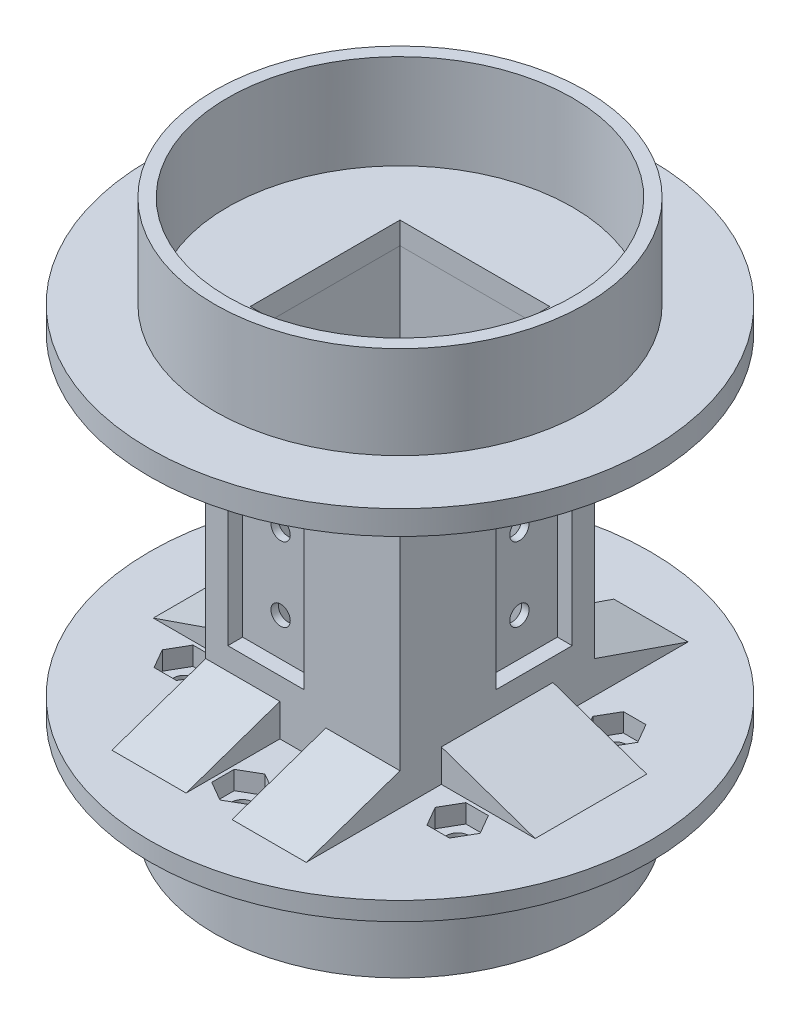
SolidWorks part; units mm, degrees
other "Markup1"
sketch "Sketch32" plane through (-67.5, -120, 67.5) normal (-0.5, 0, 0.866) x (0.866, 0, 0.5)
material "PLA"
ref_plane "Front Plane" through (0, 0, 0) normal (0, 0, 1) x (1, 0, 0)
ref_plane "Top Plane" through (0, 0, 0) normal (0, 1, 0) x (1, 0, 0)
ref_plane "Right Plane" through (0, 0, 0) normal (1, 0, 0) x (0, 0, -1)
sketch "Sketch1" plane through (0, 0, 0) normal (0, 1, 0) x (1, 0, 0)
  circle A0 centre (0, 0) radius 51.5
  circle A1 centre (0, 0) radius 46.5
  dimension "D1" = 103
  dimension "D2" = 93
extrude "Boss-Extrude1" add sketch "Sketch1" along normal blind 41
sketch "Sketch2" plane through (0, 0, 0) normal (0, -1, 0) x (1, 0, 0)
  circle A0 centre (0, 0) radius 46.5
  circle A1 centre (0, 0) radius 75
  dimension "D1" = 150
extrude "Boss-Extrude2" add sketch "Sketch2" along normal blind 5
sketch "Sketch3" plane through (0, -5, 0) normal (0, -1, 0) x (1, 0, 0)
  line L5 (-20.2, -20.2) -> (20.2, 20.2) construction
  line L6 (-20.2, 20.2) -> (20.2, -20.2) construction
  circle A0 centre (0, 0) radius 46.5
  point P0 (0, 0)
  dimension "D1" = 40.4
  dimension "D2" = 40.4
extrude "Boss-Extrude3" add sketch "Sketch3" against normal up to surface (5 mm away) up to face at (0, 0, 51.5)
sketch "Sketch4" plane through (0, 0, 0) normal (0, 1, 0) x (1, 0, 0)
  line L1 (-20.2, -20.2) -> (20.2, -20.2)
  line L2 (-20.2, -20.2) -> (-20.2, 20.2)
  line L3 (-20.2, 20.2) -> (20.2, 20.2)
  line L4 (20.2, -20.2) -> (20.2, 20.2)
  line L5 (-20.2, -20.2) -> (20.2, 20.2) construction
  line L6 (-20.2, 20.2) -> (20.2, -20.2) construction
  point P0 (0, 0)
  dimension "D1" = 40.4
  dimension "D2" = 40.4
extrude "Cut-Extrude1" cut sketch "Sketch4" against normal blind 6
sketch "Sketch5" plane through (0, -5, 0) normal (0, -1, 0) x (1, 0, 0)
  line L1 (-20.2, -20.2) -> (20.2, -20.2)
  line L2 (-20.2, -20.2) -> (-20.2, 20.2)
  line L3 (-20.2, 20.2) -> (20.2, 20.2)
  line L4 (20.2, -20.2) -> (20.2, 20.2)
  line L5 (-20.2, -20.2) -> (20.2, 20.2) construction
  line L6 (-20.2, 20.2) -> (20.2, -20.2) construction
  line L7 (-26.2, -26.2) -> (26.2, -26.2)
  line L8 (-26.2, -26.2) -> (-26.2, 26.2)
  line L9 (-26.2, 26.2) -> (26.2, 26.2)
  line L10 (26.2, -26.2) -> (26.2, 26.2)
  line L11 (-26.2, -26.2) -> (26.2, 26.2) construction
  line L12 (-26.2, 26.2) -> (26.2, -26.2) construction
  point P0 (0, 0)
  point P7 (0, 0)
  point P12 (-20.2, 0)
  point P13 (-26.2, 0)
  dimension "D1" = 6
  dimension "D2" = 6
extrude "Boss-Extrude4" add sketch "Sketch5" along normal blind 80
sketch "Sketch8" plane through (0, -85, 0) normal (0, -1, 0) x (1, 0, 0)
  line L1 (-26.2, -26.2) -> (26.2, -26.2)
  line L2 (-26.2, -26.2) -> (-26.2, 26.2)
  line L3 (-26.2, 26.2) -> (26.2, 26.2)
  line L4 (26.2, -26.2) -> (26.2, 26.2)
  line L5 (-26.2, -26.2) -> (26.2, 26.2) construction
  line L6 (-26.2, 26.2) -> (26.2, -26.2) construction
  point P0 (0, 0)
extrude "Boss-Extrude5" add sketch "Sketch8" along normal blind 5
sketch "Sketch9" plane through (0, 0, 0) normal (0, 1, 0) x (1, 0, 0)
  circle A0 centre (0, 0) radius 75
  circle A1 centre (0, 0) radius 51.5
extrude "Cut-Extrude4" cut sketch "Sketch9" against normal blind 1
sketch "Sketch10" plane through (0, -5, 0) normal (0, -1, 0) x (1, 0, 0)
  line L1 (-26.2, -26.2) -> (26.2, -26.2)
  line L2 (-26.2, -26.2) -> (-26.2, 26.2)
  line L3 (-26.2, 26.2) -> (26.2, 26.2)
  line L4 (26.2, -26.2) -> (26.2, 26.2)
  line L5 (-26.2, -26.2) -> (26.2, 26.2) construction
  line L6 (-26.2, 26.2) -> (26.2, -26.2) construction
  circle A0 centre (0, 0) radius 75
extrude "Boss-Extrude6" add sketch "Sketch10" along normal blind 1
sketch "Sketch11" plane through (0, 41, 0) normal (0, 1, 0) x (1, 0, 0)
  circle A0 centre (0, 0) radius 46.5
  circle A1 centre (0, 0) radius 51.5
extrude "Cut-Extrude5" cut sketch "Sketch11" against normal blind 13 and the other way through all
sketch "Sketch12" plane through (0, -85, 0) normal (0, 1, 0) x (1, 0, 0)
  line L1 (-20.2, -20.2) -> (20.2, -20.2)
  line L2 (-20.2, -20.2) -> (-20.2, 20.2)
  line L3 (-20.2, 20.2) -> (20.2, 20.2)
  line L4 (20.2, -20.2) -> (20.2, 20.2)
  line L5 (-20.2, -20.2) -> (20.2, 20.2) construction
  line L6 (-20.2, 20.2) -> (20.2, -20.2) construction
  point P0 (0, 0)
extrude "Cut-Extrude6" cut sketch "Sketch12" against normal blind 1
sketch "Sketch13" plane through (0, -90, 0) normal (0, -1, 0) x (1, 0, 0)
  line L1 (-26.2, -26.2) -> (26.2, -26.2)
  line L2 (-26.2, -26.2) -> (-26.2, 26.2)
  line L3 (-26.2, 26.2) -> (26.2, 26.2)
  line L4 (26.2, -26.2) -> (26.2, 26.2)
  line L5 (-26.2, -26.2) -> (26.2, 26.2) construction
  line L6 (-26.2, 26.2) -> (26.2, -26.2) construction
  point P0 (0, 0)
extrude "Boss-Extrude7" add sketch "Sketch13" along normal blind 1
sketch "Sketch6" plane through (0, 0, 26.2) normal (0, 0, 1) x (1, 0, 0)
  line L0 (-10, -6) -> (-10, -86) construction
  line L3 (26.2, -6) -> (-26.2, -6) construction
  line L4 (-20.25, -76.25) -> (0.25, -76.25)
  line L5 (-20.25, -76.25) -> (-20.25, -15.75)
  line L6 (-20.25, -15.75) -> (0.25, -15.75)
  line L7 (0.25, -76.25) -> (0.25, -15.75)
  line L8 (-20.25, -76.25) -> (0.25, -15.75) construction
  line L9 (-20.25, -15.75) -> (0.25, -76.25) construction
  line L10 (-26.2, -91) -> (-26.2, -6) construction
  point P6 (-10, -46)
  dimension "D1" = 20.5
  dimension "D2" = 60.5
  dimension "D3" = 9.75
  dimension "D4" = 5.95
extrude "Cut-Extrude2" cut sketch "Sketch6" against normal blind 4
sketch "Sketch7" plane through (0, 0, 22.2) normal (0, 0, 1) x (1, 0, 0)
  line L0 (0.25, -15.75) -> (-20.25, -15.75) construction
  circle A0 centre (-10, -26) radius 2.6
  circle A1 centre (-10, -46) radius 2.6
  circle A2 centre (-10, -66) radius 2.6
  point P10 (-10, -15.75)
  dimension "D1" = 5.2
  dimension "D2" = 5.2
  dimension "D3" = 5.2
  dimension "D4" = 10.25
  dimension "D5" = 20
  dimension "D6" = 20
  dimension "D7" = 0
extrude "Cut-Extrude3" cut sketch "Sketch7" against normal blind 2
sketch "Sketch14" plane through (-26.2, 0, 0) normal (-1, 0, 0) x (0, 0, 1)
  line L0 (26.2, -6) -> (-26.2, -6) construction
  line L1 (-0.25, -76.25) -> (20.25, -76.25)
  line L2 (-0.25, -76.25) -> (-0.25, -15.75)
  line L3 (-0.25, -15.75) -> (20.25, -15.75)
  line L4 (20.25, -76.25) -> (20.25, -15.75)
  line L5 (-0.25, -76.25) -> (20.25, -15.75) construction
  line L6 (-0.25, -15.75) -> (20.25, -76.25) construction
  line L7 (26.2, -91) -> (26.2, -6) construction
  point P0 (10, -46)
  dimension "D1" = 20.5
  dimension "D2" = 60.5
  dimension "D3" = 9.75
  dimension "D4" = 5.95
extrude "Cut-Extrude7" cut sketch "Sketch14" against normal blind 4
sketch "Sketch15" plane through (-22.2, 0, 0) normal (-1, 0, 0) x (0, 0, 1)
  line L0 (20.25, -15.75) -> (-0.25, -15.75) construction
  line L1 (-0.25, -15.75) -> (-0.25, -76.25) construction
  circle A0 centre (10, -26) radius 2.6
  circle A1 centre (10, -46) radius 2.6
  circle A2 centre (10, -66) radius 2.6
  dimension "D1" = 5.2
  dimension "D2" = 5.2
  dimension "D3" = 5.2
  dimension "D4" = 10.25
  dimension "D5" = 20
  dimension "D6" = 20
  dimension "D7" = 10.25
extrude "Cut-Extrude8" cut sketch "Sketch15" against normal blind 4
pattern_circular "CirPattern1" count 2 over 360 about axis through (0, 0, 0) along (0, 1, 0) of "Cut-Extrude2", "Cut-Extrude3"
pattern_circular "CirPattern2" count 2 over 360 about axis through (0, 0, 0) along (0, 1, 0) of "Cut-Extrude7", "Cut-Extrude8"
sketch "Sketch16" plane through (0, -1, 0) normal (0, 1, 0) x (1, 0, 0)
  circle A0 centre (0, 0) radius 75
  circle A1 centre (0, 0) radius 67.5
  dimension "D1" = 135
extrude "Cut-Extrude9" cut sketch "Sketch16" against normal blind 14
sketch "Sketch17" plane through (0, -91, 0) normal (0, -1, 0) x (1, 0, 0)
  circle A0 centre (0, 0) radius 67.5
extrude "Boss-Extrude8" add sketch "Sketch17" along normal blind 5
sketch "Sketch19" plane through (-26.2, 0, 0) normal (-1, 0, 0) x (0, 0, 1)
  line L0 (-26.2, -14.75) -> (26.2, -14.75) construction
  line L1 (-26.2, -91) -> (-26.2, -6) construction
  line L2 (26.2, -91) -> (26.2, -6) construction
  line L3 (20.25, -15.75) -> (-0.25, -15.75) construction
  line L4 (26.2, -14.75) -> (51.5, -6)
  line L5 (-67.5, -6) -> (67.5, -6) construction
  line L7 (26.2, -14.75) -> (26.2, -6)
  line L8 (26.2, -6) -> (51.5, -6)
  point P14 (51.5, -1)
  dimension "D1" = 1
sketch "Sketch23" plane through (26.2, 0, 0) normal (1, 0, 0) x (0, 0, -1)
  line L0 (67.5, -91) -> (-67.5, -91) construction
  line L1 (-26.2, -91) -> (-26.2, -6) construction
  line L2 (-51.5, -91) -> (-26.2, -82.25)
  line L3 (-26.2, -82.25) -> (-26.2, -91)
  line L4 (-26.2, -91) -> (-51.5, -91)
  point P0 (-51.5, -91)
  point P1 (-26.2, -82.25)
  point P11 (-51.5, -6)
  dimension "D1" = 8.75
sketch "Sketch25" plane through (-26.2, 0, 0) normal (-1, 0, 0) x (0, 0, 1)
  line L0 (-26.2, -82.25) -> (-51.5, -91)
  line L1 (67.5, -91) -> (-67.5, -91) construction
  line L2 (-51.5, -91) -> (-26.2, -91)
  line L3 (-26.2, -91) -> (-26.2, -82.25)
  point P0 (-51.5, -6)
sketch "Sketch27" plane through (0, -86, 0) normal (0, 1, 0) x (1, 0, 0)
  line L0 (12.6, 22.2) -> (7.4, 22.2) construction
  line L1 (12.6, 22.2) -> (7.4, 22.2)
  line L2 (4.5, 20.2) -> (15.5, 20.2)
  line L3 (20.2, 20.2) -> (-20.2, 20.2) construction
  line L4 (-22.2, -7.4) -> (-22.2, -12.6) construction
  line L5 (-12.6, -22.2) -> (-7.4, -22.2) construction
  line L6 (22.2, 7.4) -> (22.2, 12.6) construction
  line L7 (-22.2, -7.4) -> (-22.2, -12.6)
  line L8 (-12.6, -22.2) -> (-7.4, -22.2)
  line L9 (22.2, 7.4) -> (22.2, 12.6)
  line L10 (20.2, 4.5) -> (20.2, 15.5)
  line L11 (20.2, -20.2) -> (20.2, 20.2) construction
  line L12 (-20.2, -15.5) -> (-20.2, -4.5)
  line L13 (4.5, 20.2) -> (15.5, 20.2)
  line L14 (4.5, 20.2) -> (4.5, 16.2)
  line L15 (4.5, 16.2) -> (15.5, 16.2)
  line L16 (15.5, 20.2) -> (15.5, 16.2)
  line L17 (20.2, 15.5) -> (16.2, 15.5)
  line L18 (20.2, 15.5) -> (20.2, 4.5)
  line L19 (20.2, 4.5) -> (16.2, 4.5)
  line L20 (16.2, 15.5) -> (16.2, 4.5)
  line L22 (-20.2, 20.2) -> (-20.2, -20.2) construction
  line L23 (-15.5, -20.2) -> (-4.5, -20.2)
  line L24 (-20.2, -15.5) -> (-16.2, -15.5)
  line L25 (-20.2, -15.5) -> (-20.2, -4.5)
  line L26 (-20.2, -4.5) -> (-16.2, -4.5)
  line L27 (-16.2, -15.5) -> (-16.2, -4.5)
  line L30 (-15.5, -20.2) -> (-4.5, -20.2)
  line L31 (-15.5, -20.2) -> (-15.5, -16.2)
  line L32 (-15.5, -16.2) -> (-4.5, -16.2)
  line L33 (-4.5, -20.2) -> (-4.5, -16.2)
  point P2 (22.2, 10)
  point P7 (10, 20.2)
  point P8 (10, 22.2)
  point P20 (20.2, 10)
  point P24 (-22.2, -10)
  point P27 (-20.2, -10)
  point P28 (-10, -22.2)
  point P37 (-10, -20.2)
  line M9 (20.2, -20.2) -> (20.2, 20.2)
  line M10 (20.2, 20.2) -> (-20.2, 20.2)
  line M11 (-20.2, 20.2) -> (-20.2, -20.2)
  line M12 (-20.2, -20.2) -> (20.2, -20.2)
  dimension "D1" = 11
  dimension "D2" = 11
  dimension "D3" = 4
  dimension "D4" = 4
  dimension "D5" = 11
  dimension "D6" = 4
  dimension "D7" = 11
  dimension "D8" = 4
extrude "Cut-Extrude10" cut sketch "Sketch27" against normal blind 20 contours L16 L14 L15 M10 | L17 L20 L19 M9 | L24 L27 L26 M11 | L33 L32 L31 M12
sketch "Sketch28" plane through (0, 28, 0) normal (0, 1, 0) x (1, 0, 0)
  circle A0 centre (0, 0) radius 50
  circle A1 centre (0, 0) radius 51.5
  dimension "D1" = 100
extrude "Cut-Extrude11" cut sketch "Sketch28" against normal up to surface (29 mm away) up to face at (0, -1, 51.5)
sketch "Sketch29" plane through (0, -96, 0) normal (0, -1, 0) x (1, 0, 0)
  circle A0 centre (0, 0) radius 50
  circle A1 centre (0, 0) radius 45
  dimension "D1" = 100
  dimension "D2" = 90
extrude "Boss-Extrude17" add sketch "Sketch29" along normal blind 24
sketch "Sketch30" plane through (0, -96, 0) normal (0, -1, 0) x (1, 0, 0)
  line L0 (0.25, 22.2) -> (0.25, 26.2) construction
  line L1 (-20.25, 22.2) -> (-20.25, 26.2) construction
  line L2 (0.25, 22.2) -> (0.25, 26.2)
  line L3 (-20.25, 22.2) -> (-20.25, 26.2)
  line L4 (-20.25, 22.2) -> (0.25, 22.2) construction
  line L5 (-4.5, 20.2) -> (-15.5, 20.2) construction
  line L6 (-15.75, 15.95) -> (-4.25, 15.95)
  line L7 (-15.75, 15.95) -> (-15.75, 20.45)
  line L8 (-15.75, 20.45) -> (-4.25, 20.45)
  line L9 (-4.25, 15.95) -> (-4.25, 20.45)
  line L10 (-15.75, 15.95) -> (-4.25, 20.45) construction
  line L11 (-15.75, 20.45) -> (-4.25, 15.95) construction
  line L12 (-15.5, 16.2) -> (-15.5, 20.2) construction
  line L13 (-20.2, 15.5) -> (-20.2, 4.5) construction
  line L14 (-20.45, 4.25) -> (-15.95, 4.25)
  line L15 (-20.45, 4.25) -> (-20.45, 15.75)
  line L16 (-20.45, 15.75) -> (-15.95, 15.75)
  line L17 (-15.95, 4.25) -> (-15.95, 15.75)
  line L18 (-20.45, 4.25) -> (-15.95, 15.75) construction
  line L19 (-20.45, 15.75) -> (-15.95, 4.25) construction
  line L20 (-16.2, 4.5) -> (-20.2, 4.5) construction
  point P4 (-10, 18.2)
  point P13 (-18.2, 10)
  line M12 (-15.5, 20.2) -> (-4.5, 20.2)
  line M13 (-4.5, 20.2) -> (-4.5, 16.2)
  line M14 (-4.5, 16.2) -> (-15.5, 16.2)
  line M15 (-15.5, 16.2) -> (-15.5, 20.2)
  line M16 (-20.2, 15.5) -> (-16.2, 15.5)
  line M17 (-16.2, 15.5) -> (-16.2, 4.5)
  line M18 (-16.2, 4.5) -> (-20.2, 4.5)
  line M19 (-20.2, 4.5) -> (-20.2, 15.5)
  dimension "D1" = 4.5
  dimension "D2" = 0.25
  dimension "D3" = 11.5
  dimension "D4" = 0.25
  dimension "D5" = 4.5
  dimension "D6" = 0.25
  dimension "D7" = 0.25
  dimension "D8" = 11.5
extrude "Cut-Extrude12" cut sketch "Sketch30" against normal blind 10 contours M16 M19 M18 M17 | M12 M15 M14 M13 | L6 L9 L8 L7 M15 M12 M13 M14 | L14 L17 L16 L15 M19 M16 M17 M18
sketch "Sketch31" plane through (0, -96, 0) normal (0, -1, 0) x (1, 0, 0)
  line L0 (16.2, -15.5) -> (20.2, -15.5) construction
  line L1 (15.95, -15.75) -> (20.45, -15.75)
  line L2 (15.95, -15.75) -> (15.95, -4.25)
  line L3 (15.95, -4.25) -> (20.45, -4.25)
  line L4 (20.45, -15.75) -> (20.45, -4.25)
  line L5 (15.95, -15.75) -> (20.45, -4.25) construction
  line L6 (15.95, -4.25) -> (20.45, -15.75) construction
  line L7 (4.25, -20.45) -> (15.75, -20.45)
  line L8 (4.25, -20.45) -> (4.25, -15.95)
  line L9 (4.25, -15.95) -> (15.75, -15.95)
  line L10 (15.75, -20.45) -> (15.75, -15.95)
  line L11 (4.25, -20.45) -> (15.75, -15.95) construction
  line L12 (4.25, -15.95) -> (15.75, -20.45) construction
  line L13 (20.2, -15.5) -> (20.2, -4.5) construction
  line L14 (4.5, -16.2) -> (4.5, -20.2) construction
  line L15 (15.5, -16.2) -> (4.5, -16.2) construction
  point P0 (18.2, -10)
  point P5 (10, -18.2)
  dimension "D1" = 4.5
  dimension "D2" = 11.5
  dimension "D3" = 4.5
  dimension "D4" = 11.5
  dimension "D5" = 0.25
  dimension "D6" = 0.25
  dimension "D7" = 0.25
  dimension "D8" = 0.25
extrude "Cut-Extrude13" cut sketch "Sketch31" against normal blind 10
sketch "Sketch33" plane through (0, -96, 0) normal (0, -1, 0) x (1, 0, 0)
  circle A0 centre (0, 0) radius 35
  circle A1 centre (0, 0) radius 45
  dimension "D1" = 70
extrude "Boss-Extrude18" add sketch "Sketch33" along normal up to surface (24 mm away) up to face at (0, -120, -50)
sketch "Sketch34" plane through (0, -120, 0) normal (0, -1, 0) x (1, 0, 0)
  circle A0 centre (0, 0) radius 35
  circle A1 centre (0, 0) radius 50
extrude "Boss-Extrude19" add sketch "Sketch34" along normal blind 1.5
sketch "Sketch35" plane through (0, -121.5, 0) normal (0, -1, 0) x (1, 0, 0)
  circle A0 centre (0, 0) radius 42.5
  circle A1 centre (0, 42.5) radius 2.95
  circle A2 centre (36.8061, 21.25) radius 2.95
  circle A3 centre (36.8061, -21.25) radius 2.95
  circle A4 centre (0, -42.5) radius 2.95
  circle A5 centre (-36.8061, -21.25) radius 2.95
  circle A6 centre (-36.8061, 21.25) radius 2.95
  point P17 (0, 0)
  dimension "D1" = 85
  dimension "D2" = 5.9
  dimension "D3" = 6
extrude "Cut-Extrude14" cut sketch "Sketch35" against normal blind 45 contours A0 A1 | A0 A1 | A2 | A3 | A4 | A5 | A6
extrude "Boss-Extrude20" add sketch "Sketch25" against normal blind 20
sketch "Sketch37" plane through (26.2, 0, 0) normal (1, 0, 0) x (0, 0, -1)
  line L3 (26.2, -82.25) -> (26.2, -91)
  line L4 (26.2, -91) -> (51.5, -91)
  line L5 (51.5, -91) -> (26.2, -82.25)
  line L6 (26.2, -82.25) -> (26.2, -91)
  line L7 (26.2, -91) -> (51.5, -91)
  line L8 (51.5, -91) -> (26.2, -82.25)
  dimension "D1" = 0
extrude "Boss-Extrude21" add sketch "Sketch37" against normal blind 20
ref_plane "Plane1" through (0, 0, 0) normal (0, 0, -1) x (-1, 0, 0)
sketch "Sketch39" plane through (0, 0, 0) normal (0, 0, -1) x (-1, 0, 0)
  line L1 (-26.2, -91) -> (-26.2, -82.25) construction
  line L3 (-51.5, -91) -> (-26.2, -91)
  line L4 (-26.2, -91) -> (-26.2, -82.25)
  line L5 (-26.2, -82.25) -> (-51.5, -91)
extrude "Boss-Extrude22" add sketch "Sketch39" along normal mid plane 30.1
extrude "Boss-Extrude23" add sketch "Sketch23" against normal blind 20
sketch "Sketch40" plane through (-26.2, 0, 0) normal (-1, 0, 0) x (0, 0, 1)
  line L3 (26.2, -91) -> (51.5, -91)
  line L4 (51.5, -91) -> (26.2, -82.25)
  line L5 (26.2, -82.25) -> (26.2, -91)
  line L6 (26.2, -91) -> (51.5, -91)
  line L7 (51.5, -91) -> (26.2, -82.25)
  line L8 (26.2, -82.25) -> (26.2, -91)
  dimension "D1" = 0
extrude "Boss-Extrude24" add sketch "Sketch40" against normal blind 20
ref_plane "Plane2" through (0, 0, 0) normal (0, 0, 1) x (1, 0, 0)
sketch "Sketch41" plane through (0, 0, 0) normal (0, 0, 1) x (1, 0, 0)
  line L3 (-51.5, -91) -> (-26.2, -91)
  line L4 (-26.2, -91) -> (-26.2, -82.25)
  line L5 (-26.2, -82.25) -> (-51.5, -91)
extrude "Boss-Extrude25" add sketch "Sketch41" along normal mid plane 30.1
sketch "Sketch38" plane through (0, -91, 0) normal (0, 1, 0) x (1, 0, 0)
  line L0 (6.2, 26.2) -> (26.2, 26.2) construction
  line L1 (39.8372, -16) -> (33.775, -16)
  line L2 (33.775, -16) -> (30.7439, -21.25)
  line L3 (30.7439, -21.25) -> (33.775, -26.5)
  line L4 (33.775, -26.5) -> (39.8372, -26.5)
  line L5 (39.8372, -26.5) -> (42.8683, -21.25)
  line L6 (42.8683, -21.25) -> (39.8372, -16)
  line L7 (39.8372, 26.5) -> (33.775, 26.5)
  line L8 (33.775, 26.5) -> (30.7439, 21.25)
  line L9 (30.7439, 21.25) -> (33.775, 16)
  line L10 (33.775, 16) -> (39.8372, 16)
  line L11 (39.8372, 16) -> (42.8683, 21.25)
  line L12 (42.8683, 21.25) -> (39.8372, 26.5)
  line L13 (26.2, -15.05) -> (47.6541, -15.05) construction
  line L14 (26.2, 51.5) -> (26.2, 15.05) construction
  line L15 (26.2, 15.05) -> (47.6541, 15.05) construction
  line L16 (6.2, -51.5) -> (6.2, -26.2) construction
  line L17 (5.25, -45.5311) -> (5.25, -39.4689)
  line L18 (5.25, -39.4689) -> (0, -36.4378)
  line L19 (0, -36.4378) -> (-5.25, -39.4689)
  line L20 (-5.25, -39.4689) -> (-5.25, -45.5311)
  line L21 (-5.25, -45.5311) -> (0, -48.5622)
  line L22 (0, -48.5622) -> (5.25, -45.5311)
  line L24 (-39.8372, -26.5) -> (-33.775, -26.5)
  line L25 (-33.775, -26.5) -> (-30.7439, -21.25)
  line L26 (-30.7439, -21.25) -> (-33.775, -16)
  line L27 (-33.775, -16) -> (-39.8372, -16)
  line L28 (-39.8372, -16) -> (-42.8683, -21.25)
  line L29 (-42.8683, -21.25) -> (-39.8372, -26.5)
  line L30 (-51.5, -15.05) -> (-26.2, -15.05) construction
  line L31 (-51.5, 15.05) -> (-26.2, 15.05) construction
  line L32 (-39.8372, 16) -> (-33.775, 16)
  line L33 (-33.775, 16) -> (-30.7439, 21.25)
  line L34 (-30.7439, 21.25) -> (-33.775, 26.5)
  line L35 (-33.775, 26.5) -> (-39.8372, 26.5)
  line L36 (-39.8372, 26.5) -> (-42.8683, 21.25)
  line L37 (-42.8683, 21.25) -> (-39.8372, 16)
  line L38 (-6.2, 51.5) -> (-6.2, 26.2) construction
  line L39 (0, 48.5622) -> (-5.25, 45.5311)
  line L40 (-5.25, 45.5311) -> (-5.25, 39.4689)
  line L41 (-5.25, 39.4689) -> (0, 36.4378)
  line L42 (0, 36.4378) -> (5.25, 39.4689)
  line L43 (5.25, 39.4689) -> (5.25, 45.5311)
  line L44 (5.25, 45.5311) -> (0, 48.5622)
  circle A0 centre (36.8061, -21.25) radius 5.25 construction
  circle A1 centre (36.8061, 21.25) radius 5.25 construction
  circle A2 centre (0, -42.5) radius 5.25 construction
  circle A3 centre (-36.8061, -21.25) radius 5.25 construction
  circle A4 centre (-36.8061, 21.25) radius 5.25 construction
  circle A5 centre (0, 42.5) radius 5.25 construction
  dimension "D1" = 10.5
  dimension "D2" = 10.5
  dimension "D3" = 0.95
  dimension "D4" = 0.95
  dimension "D5" = 10.5
  dimension "D6" = 10.5
  dimension "D7" = 10.5
  dimension "D8" = 10.5
extrude "Cut-Extrude15" cut sketch "Sketch38" against normal blind 5
sketch "Sketch42" plane through (0, 28, 0) normal (0, 1, 0) x (1, 0, 0)
  circle A0 centre (0, 0) radius 50
  circle A1 centre (0, 0) radius 46.5
extrude "Cut-Extrude16" cut sketch "Sketch42" against normal blind 4
sketch "Sketch43" plane through (0, -1, 0) normal (0, 1, 0) x (1, 0, 0)
  circle A0 centre (0, 0) radius 67.5
  circle A1 centre (0, 0) radius 50
extrude "Cut-Extrude17" cut sketch "Sketch43" against normal blind 0.5
sketch "Sketch44" plane through (0, -1.5, 0) normal (0, 1, 0) x (1, 0, 0)
  circle A0 centre (0, 0) radius 50
  circle A1 centre (0, 0) radius 67.5
extrude "Boss-Extrude26" add sketch "Sketch44" along normal blind 2
sketch "Sketch45" plane through (0, 24, 0) normal (0, 1, 0) x (1, 0, 0)
  circle A0 centre (0, 0) radius 46.5
  circle A1 centre (0, 0) radius 50
extrude "Boss-Extrude27" add sketch "Sketch45" along normal blind 1.5
sketch "Sketch46" plane through (0, -96, 0) normal (0, -1, 0) x (1, 0, 0)
  line L1 (-15.75, 15.95) -> (-4.25, 15.95)
  line L2 (-15.75, 15.95) -> (-15.75, 13.95)
  line L3 (-15.75, 13.95) -> (-4.25, 13.95)
  line L4 (-4.25, 15.95) -> (-4.25, 13.95)
  line L5 (-15.95, 4.25) -> (-13.95, 4.25)
  line L6 (-15.95, 4.25) -> (-15.95, 15.75)
  line L7 (-15.95, 15.75) -> (-13.95, 15.75)
  line L8 (-13.95, 4.25) -> (-13.95, 15.75)
  line L9 (15.75, -15.95) -> (4.25, -15.95)
  line L10 (15.75, -15.95) -> (15.75, -13.95)
  line L11 (15.75, -13.95) -> (4.25, -13.95)
  line L12 (4.25, -15.95) -> (4.25, -13.95)
  line L13 (15.95, -4.25) -> (13.95, -4.25)
  line L14 (15.95, -4.25) -> (15.95, -15.75)
  line L15 (15.95, -15.75) -> (13.95, -15.75)
  line L16 (13.95, -4.25) -> (13.95, -15.75)
  dimension "D1" = 2
  dimension "D2" = 2
  dimension "D3" = 2
  dimension "D4" = 2
extrude "Cut-Extrude18" cut sketch "Sketch46" against normal up to surface (10 mm away) contours L16 L15 L14 L13 | L11 L12 L9 L10 | L3 L4 L1 L2 | L8 L7 L6 L5 up to face at (0, -86, 0)
ref_plane "Plane3" through (0, -6, 0) normal (0, 1, 0) x (1, 0, 0)
sketch "Sketch47" plane through (0, 0, 0) normal (0, 0, 1) x (1, 0, 0)
  line L0 (55, -6) -> (-55, -6) construction
  line L1 (-67.5, -6) -> (67.5, -6) construction
  line L2 (26.2, -6) -> (-26.2, -6)
  line L3 (-26.2, -14.75) -> (-26.2, -6) construction
  line L4 (-26.2, -14.75) -> (-26.2, -6) construction
  point P0 (26.2, -6)
split "Split1" trim tools "Sketch47" bodies to split 148 resulting bodies 149 150
